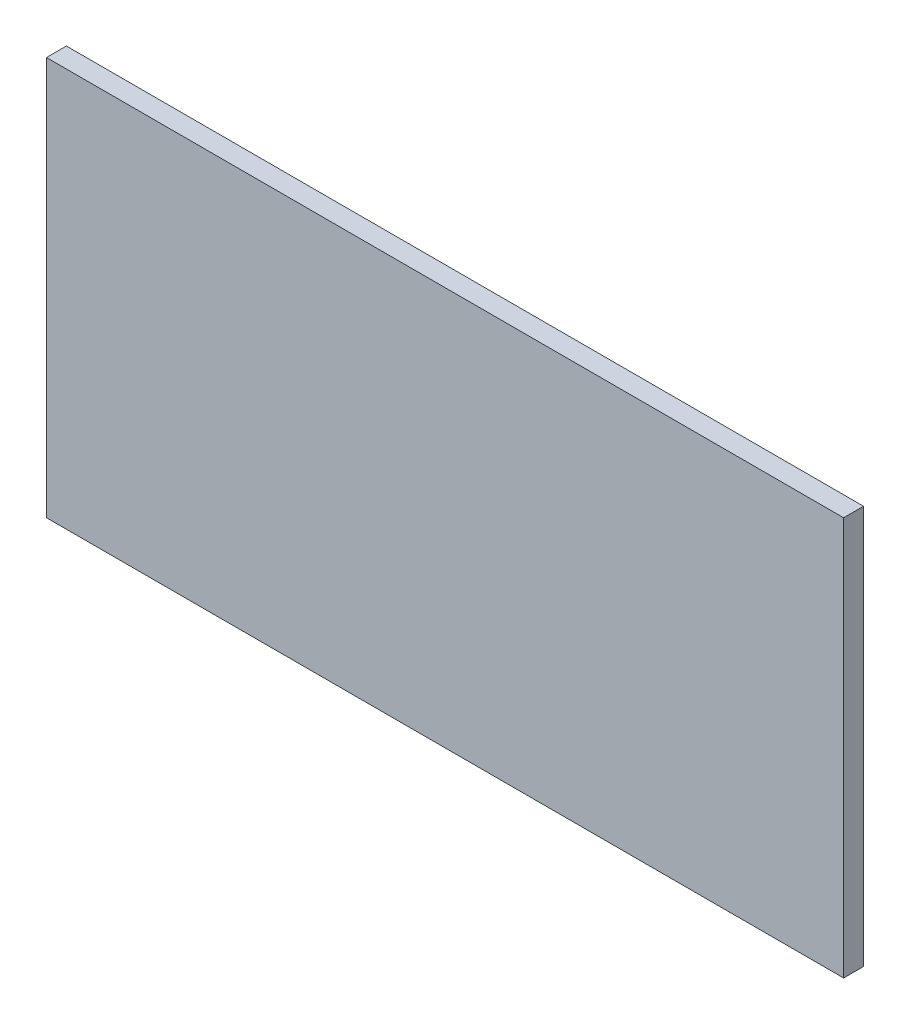
SolidWorks part; units mm, degrees
ref_plane "Front Plane" through (0, 0, 0) normal (0, 0, 1) x (1, 0, 0)
ref_plane "Top Plane" through (0, 0, 0) normal (0, 1, 0) x (1, 0, 0)
ref_plane "Right Plane" through (0, 0, 0) normal (1, 0, 0) x (0, 0, -1)
sketch "Sketch1" plane through (0, 0, 0) normal (0, 0, 1) x (1, 0, 0)
  line L1 (0, 0) -> (1000, 0)
  line L2 (0, 0) -> (0, 500)
  line L3 (0, 500) -> (1000, 500)
  line L4 (1000, 0) -> (1000, 500)
  dimension "D1" = 1000
  dimension "D2" = 500
extrude "Boss-Extrude1" add sketch "Sketch1" along normal blind 25
sketch "Sketch2" plane through (0, 0, 0) normal (0, -1, 0) x (1, 0, 0)
  line L0 (25, 25) -> (25, 0)
  line L1 (0, 25) -> (1000, 25) construction
  line L2 (0, 0) -> (1000, 0) construction
  line L3 (975, 25) -> (975, 0)
  line L4 (0, 25) -> (0, 0) construction
  line L5 (1000, 25) -> (1000, 0) construction
  dimension "D1" = 25
  dimension "D2" = 25
split line "Split Line1"
